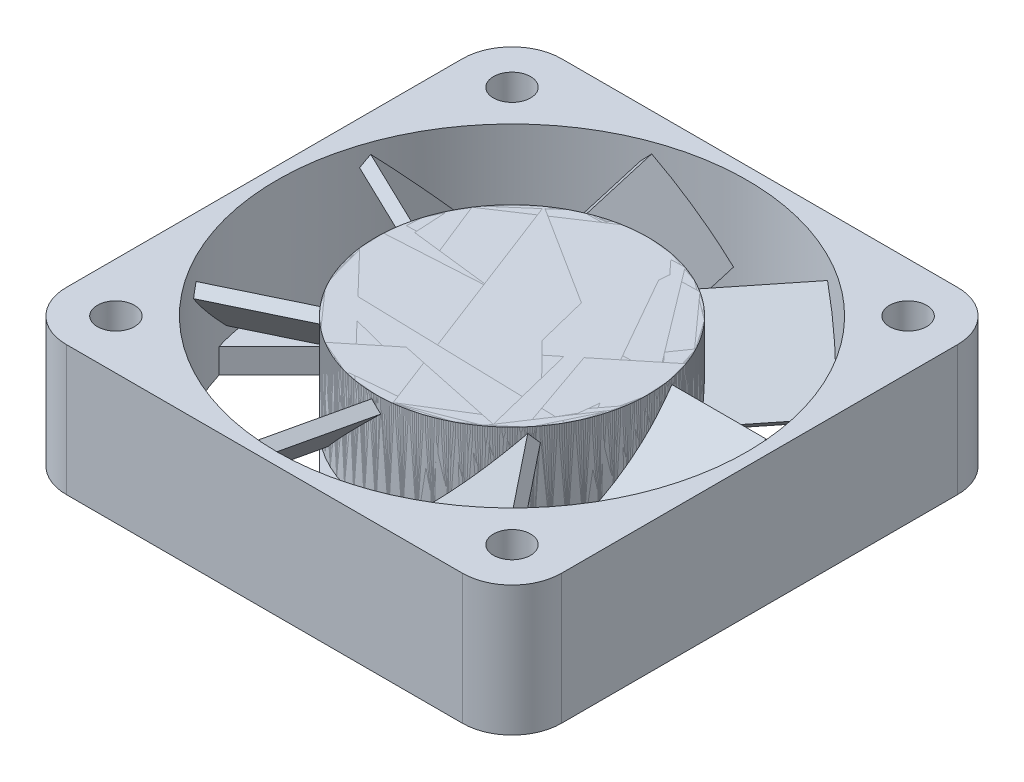
SolidWorks part; units mm, degrees
ref_plane "Front Plane" through (0, 0, 0) normal (0, 0, 1) x (1, 0, 0)
ref_plane "Top Plane" through (0, 0, 0) normal (0, 1, 0) x (1, 0, 0)
ref_plane "Right Plane" through (0, 0, 0) normal (1, 0, 0) x (0, 0, -1)
sketch "Sketch1" plane through (0, 0, 0) normal (0, 1, 0) x (1, 0, 0)
  line L0 (-20, 20) -> (20, -20) construction
  line L1 (-16, 20) -> (16, 20)
  line L2 (-20, 16) -> (-20, -16)
  line L3 (-16, -20) -> (16, -20)
  line L4 (20, 16) -> (20, -16)
  line L5 (16, 16) -> (-16, 16) construction
  line L6 (-16, 16) -> (-16, -16) construction
  line L7 (-16, -16) -> (16, -16) construction
  line L8 (16, -16) -> (16, 16) construction
  line L9 (-16, -16) -> (16, 16) construction
  circle A0 centre (0, 0) radius 19
  circle A1 centre (-16, 16) radius 1.5
  circle A2 centre (16, 16) radius 1.5
  circle A3 centre (16, -16) radius 1.5
  circle A4 centre (-16, -16) radius 1.5
  arc A5 (16, 20) -> (20, 16) centre (16, 16) cw
  arc A6 (16, -20) -> (20, -16) centre (16, -16) ccw
  arc A7 (-20, -16) -> (-16, -20) centre (-16, -16) ccw
  arc A8 (-16, 20) -> (-20, 16) centre (-16, 16) ccw
  point P17 (20, 20)
  dimension "D2" = 38
  dimension "D3" = 3
  dimension "D5" = 4
  dimension "D1" = 40
  dimension "D4" = 32
extrude "Boss-Extrude1" add sketch "Sketch1" along normal blind 10.5
sketch "Sketch2" plane through (0, 0, 0) normal (0, -1, 0) x (1, 0, 0)
  line L0 (-7.7782, 7.7782) -> (3.1763, 18.7326)
  line L1 (5.4682, 18.1961) -> (-1.8918, 10.8361)
  line L2 (0, 0) -> (0, 3.9858) construction
  line L3 (7.7782, 7.7782) -> (18.7326, -3.1763)
  line L4 (18.1961, -5.4682) -> (10.8361, 1.8918)
  line L5 (7.7782, -7.7782) -> (-3.1763, -18.7326)
  line L6 (-5.4682, -18.1961) -> (1.8918, -10.8361)
  line L7 (-7.7782, -7.7782) -> (-18.7326, 3.1763)
  line L8 (-18.1961, 5.4682) -> (-10.8361, -1.8918)
  arc A0 (-7.7782, 7.7782) -> (-10.8361, -1.8918) centre (0, 0) ccw
  circle A1 centre (0, 0) radius 19 construction
  arc A2 (5.4682, 18.1961) -> (3.1763, 18.7326) centre (0, 0) ccw
  arc A3 (18.1961, -5.4682) -> (18.7326, -3.1763) centre (0, 0) ccw
  arc A4 (-5.4682, -18.1961) -> (-3.1763, -18.7326) centre (0, 0) ccw
  arc A5 (-18.1961, 5.4682) -> (-18.7326, 3.1763) centre (0, 0) ccw
  arc A6 (7.7782, 7.7782) -> (-1.8918, 10.8361) centre (0, 0) ccw
  arc A7 (7.7782, -7.7782) -> (10.8361, 1.8918) centre (0, 0) ccw
  arc A8 (-7.7782, -7.7782) -> (1.8918, -10.8361) centre (0, 0) ccw
  point P24 (0, 0)
  dimension "D2" = 22
  dimension "D1" = 135
  dimension "D3" = 2
  dimension "D4" = 4
extrude "Boss-Extrude2" add sketch "Sketch2" against normal blind 2
sketch "Sketch3" plane through (0, 10.5, 0) normal (0, 1, 0) x (1, 0, 0)
  circle A0 centre (0, 0) radius 11
  dimension "D1" = 22
extrude "Boss-Extrude3" add sketch "Sketch3" against normal offset from surface (8 mm away) 0.5 separate body up to face at (0, 2, 0)
sketch "Sketch4" plane through (0, 0, 0) normal (1, 0, 0) x (0, 0, -1)
  line L0 (-3.5355, 4.3787) -> (2.1213, 10.0355)
  line L1 (-3.5355, 4.3787) -> (-2.8284, 3.6716)
  line L2 (2.1213, 10.0355) -> (2.8284, 9.3284)
  line L3 (-2.8284, 3.6716) -> (2.8284, 9.3284)
  line L4 (0, 0) -> (0, 6.5) construction
  line L5 (-16, 0) -> (16, 0) construction
  line L6 (0, 6.5) -> (11, 6.5) construction
  line L7 (11, 2.5) -> (11, 10.5) construction
  dimension "D1" = 45
  dimension "D2" = 1
  dimension "D3" = 8
extrude "Boss-Extrude4" add sketch "Sketch4" along normal offset from surface (18.378 mm away) 0.5
pattern_circular "CirPattern3" count 7 over 360 about axis through (0, 0, 0) along (0, 1, 0) of bodies 104
